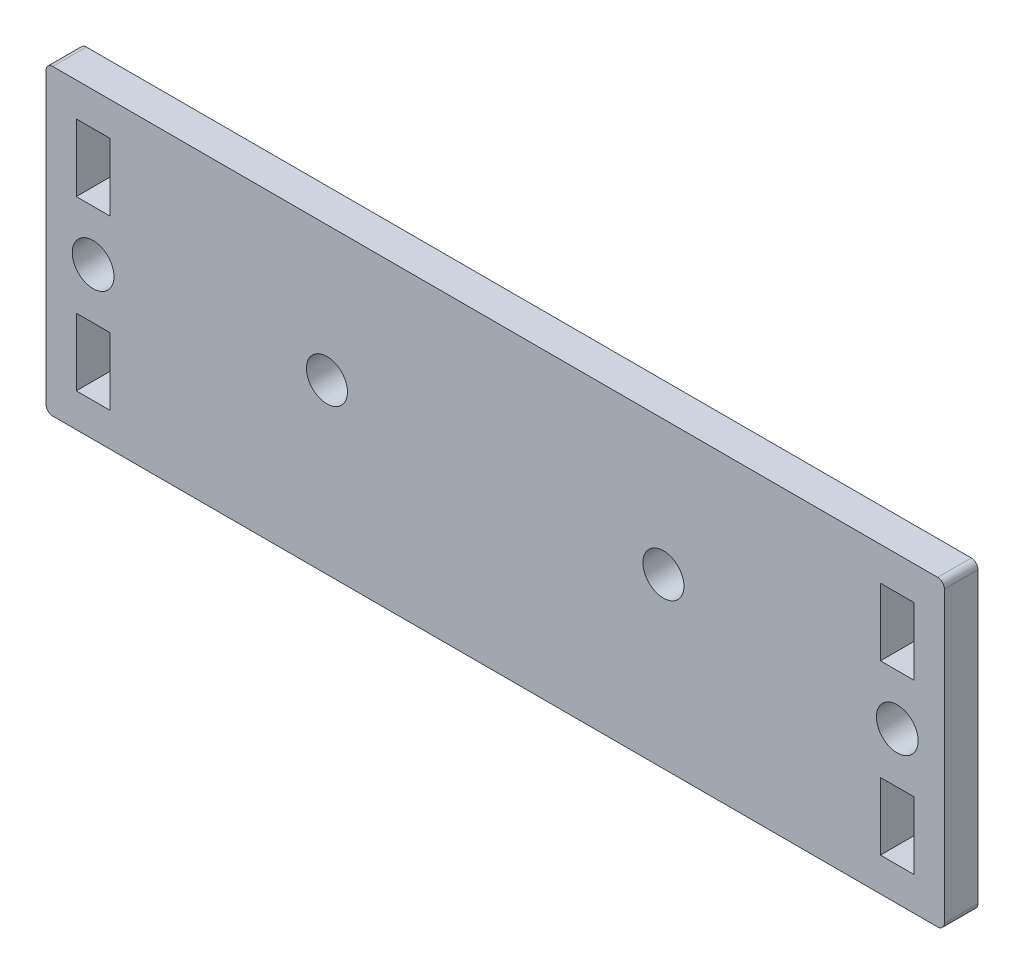
SolidWorks part; units mm, degrees
material "6061 Alloy"
ref_plane "Front Plane" through (0, 0, 0) normal (0, 0, 1) x (1, 0, 0)
ref_plane "Top Plane" through (0, 0, 0) normal (0, 1, 0) x (1, 0, 0)
ref_plane "Right Plane" through (0, 0, 0) normal (1, 0, 0) x (0, 0, -1)
sketch "Sketch1" plane through (0, 0, 0) normal (0, 0, 1) x (1, 0, 0)
  line L0 (0, 27.5) -> (0, -12.55) construction
  line L1 (-66.75, 22.5) -> (66.75, 22.5)
  line L2 (-66.75, 22.5) -> (-66.75, -22.5)
  line L3 (-66.75, -22.5) -> (66.75, -22.5)
  line L4 (66.75, 22.5) -> (66.75, -22.5)
  line L5 (-66.75, 22.5) -> (66.75, -22.5) construction
  line L6 (-66.75, -22.5) -> (66.75, 22.5) construction
  line L7 (40.05, 27.5) -> (-40.05, 27.5) construction
  line L8 (40.05, 27.5) -> (40.05, -12.55) construction
  line L9 (40.05, -12.55) -> (-40.05, -12.55) construction
  line L10 (-40.05, 27.5) -> (-40.05, -12.55) construction
  line L11 (65.75, 27.5) -> (-65.75, 27.5) construction
  line L12 (-52.75, 22.5) -> (-52.75, -8.5) construction
  line L13 (-52.75, -8.5) -> (52.75, -8.5) construction
  line L14 (52.75, 22.5) -> (52.75, -8.5) construction
  line L15 (-66.75, -12.5) -> (-52.75, -12.5) construction
  line L16 (-62.25, -7.5) -> (-57.25, -7.5)
  line L17 (-62.25, -7.5) -> (-62.25, -17.5)
  line L18 (-62.25, -17.5) -> (-57.25, -17.5)
  line L19 (-57.25, -7.5) -> (-57.25, -17.5)
  line L20 (-62.25, -7.5) -> (-57.25, -17.5) construction
  line L21 (-62.25, -17.5) -> (-57.25, -7.5) construction
  line L22 (-59.75, -12.5) -> (-59.75, 12.5) construction
  line L23 (62.25, -17.5) -> (57.25, -17.5)
  line L24 (-62.25, 17.5) -> (-57.25, 17.5)
  line L25 (-62.25, 17.5) -> (-62.25, 7.5)
  line L26 (-62.25, 7.5) -> (-57.25, 7.5)
  line L27 (-57.25, 17.5) -> (-57.25, 7.5)
  line L28 (-62.25, 17.5) -> (-57.25, 7.5) construction
  line L29 (-62.25, 7.5) -> (-57.25, 17.5) construction
  line L30 (57.25, -7.5) -> (57.25, -17.5)
  line L31 (62.25, -7.5) -> (62.25, -17.5)
  line L32 (62.25, -7.5) -> (57.25, -7.5)
  line L33 (62.25, 17.5) -> (57.25, 17.5)
  line L34 (57.25, 17.5) -> (57.25, 7.5)
  line L35 (62.25, 7.5) -> (57.25, 7.5)
  line L36 (62.25, 17.5) -> (62.25, 7.5)
  circle A0 centre (25, 2.5) radius 3.05
  circle A1 centre (-25, 2.5) radius 3.05
  circle A2 centre (-59.75, 0) radius 3.1
  circle A3 centre (59.75, 0) radius 3.1
  point P0 (0, 0)
  point P12 (0, 27.5)
  point P23 (-59.75, -12.5)
  dimension "D5" = 25
  dimension "D6" = 6.1
  dimension "D7" = 25
  dimension "D13" = 6.2
  dimension "D1" = 45
  dimension "D2" = 133.5
  dimension "D3" = 80.1
  dimension "D4" = 40.05
  dimension "D8" = 14
  dimension "D9" = 5
  dimension "D10" = 5
  dimension "D11" = 10
  dimension "D12" = 35
extrude "Boss-Extrude1" add sketch "Sketch1" along normal blind 5
fillet "Fillet1" radius 1 4 edges at (66.75, 22.5, 2.5) (66.75, -22.5, 2.5) (-66.75, -22.5, 2.5) (-66.75, 22.5, 2.5)
